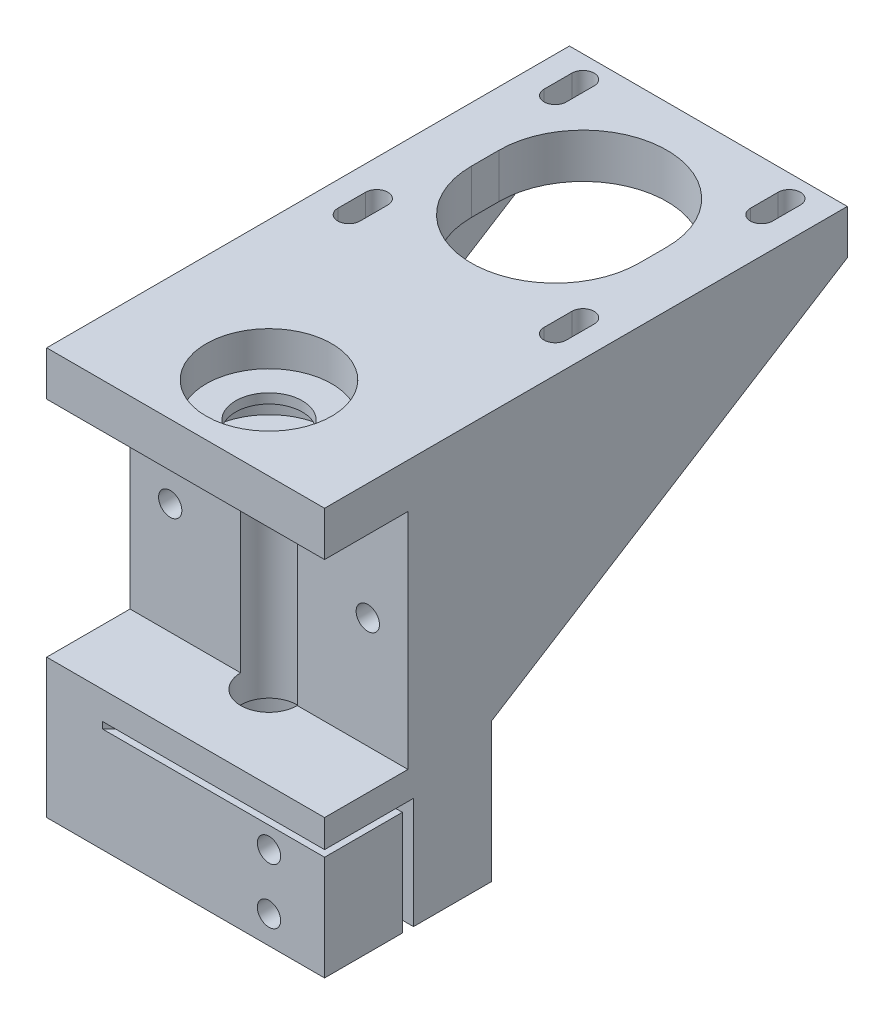
SolidWorks part; units mm, degrees
ref_plane "Front Plane" through (0, 0, 0) normal (0, 0, 1) x (1, 0, 0)
ref_plane "Top Plane" through (0, 0, 0) normal (0, 1, 0) x (1, 0, 0)
ref_plane "Right Plane" through (0, 0, 0) normal (1, 0, 0) x (0, 0, -1)
sketch "Sketch1" plane through (0, 0, 0) normal (0, 1, 0) x (1, 0, 0)
  line L1 (-25.4, -19.05) -> (25.4, -19.05)
  line L2 (-25.4, -19.05) -> (-25.4, 19.05)
  line L3 (-25.4, 19.05) -> (25.4, 19.05)
  line L4 (25.4, -19.05) -> (25.4, 19.05)
  line L5 (-25.4, -19.05) -> (25.4, 19.05) construction
  line L6 (-25.4, 19.05) -> (25.4, -19.05) construction
  circle A0 centre (0, 0) radius 13.335
  dimension "D3" = 19.05
  dimension "D2" = 25.4
  dimension "D1" = 26.67
extrude "Boss-Extrude2" add sketch "Sketch1" along normal blind 25.4
sketch "Sketch2" plane through (0, 25.4, 0) normal (0, 1, 0) x (1, 0, 0)
  line L0 (0, 0) -> (25.4, 0) construction
  line L1 (25.4, -19.05) -> (25.4, 19.05) construction
  line L2 (0, -1.27) -> (25.4, -1.27)
  line L3 (0, 1.27) -> (25.4, 1.27)
  line L4 (0, 1.27) -> (0, -1.27)
  line L5 (25.4, -1.27) -> (25.4, 1.27)
  dimension "D1" = 1.27
  dimension "D2" = 1.27
extrude "Cut-Extrude1" cut sketch "Sketch2" against normal up to next
sketch "Sketch3" plane through (0, 0, 19.05) normal (0, 0, 1) x (1, 0, 0)
  line L0 (-25.4, 25.4) -> (25.4, 25.4) construction
  line L1 (25.4, 25.4) -> (25.4, 0) construction
  line L2 (-25.4, 0) -> (25.4, 0) construction
  circle A0 centre (19.05, 19.05) radius 2.665
  circle A1 centre (19.05, 6.35) radius 2.665
  dimension "D1" = 5.33
  dimension "D2" = 6.35
  dimension "D3" = 6.35
  dimension "D4" = 6.35
  dimension "D5" = 6.35
extrude "Cut-Extrude2" cut sketch "Sketch3" against normal through all
sketch "Sketch4" plane through (0, 0, -19.05) normal (0, 0, -1) x (-1, 0, 0)
  line L1 (-19.05, 24.8235) -> (-24.05, 21.9368)
  line L2 (-24.05, 21.9368) -> (-24.05, 16.1632)
  line L3 (-24.05, 16.1632) -> (-19.05, 13.2765)
  line L4 (-19.05, 13.2765) -> (-14.05, 16.1632)
  line L5 (-14.05, 16.1632) -> (-14.05, 21.9368)
  line L6 (-14.05, 21.9368) -> (-19.05, 24.8235)
  line L7 (-19.05, 12.1235) -> (-24.05, 9.2368)
  line L8 (-24.05, 9.2368) -> (-24.05, 3.4632)
  line L9 (-24.05, 3.4632) -> (-19.05, 0.5765)
  line L10 (-19.05, 0.5765) -> (-14.05, 3.4632)
  line L11 (-14.05, 3.4632) -> (-14.05, 9.2368)
  line L12 (-14.05, 9.2368) -> (-19.05, 12.1235)
  circle A0 centre (-19.05, 19.05) radius 5 construction
  circle A1 centre (-19.05, 6.35) radius 5 construction
  dimension "D1" = 10
extrude "Cut-Extrude3" cut sketch "Sketch4" against normal blind 10
sketch "Sketch5" plane through (0, 25.4, 0) normal (0, 1, 0) x (1, 0, 0)
  line L0 (-19.05, -19.05) -> (-9.4293, -9.4293)
  line L1 (-25.4, -19.05) -> (25.4, -19.05) construction
  line L2 (-25.4, 19.05) -> (-25.4, -19.05) construction
  line L3 (25.4, -19.05) -> (25.4, -1.27) construction
  line L4 (13.2744, -1.27) -> (25.4, -1.27) construction
  line L5 (-19.05, -19.05) -> (25.4, -19.05)
  line L6 (25.4, -19.05) -> (25.4, -1.27)
  line L7 (13.2744, -1.27) -> (25.4, -1.27)
  arc A0 (13.2744, 1.27) -> (13.2744, -1.27) centre (0, 0) ccw construction
  arc A1 (-9.4293, -9.4293) -> (13.2744, -1.27) centre (0, 0) ccw
  dimension "D1" = 6.35
  dimension "D2" = 45
extrude "Cut-Extrude4" cut sketch "Sketch5" against normal blind 1.5
sketch "Sketch6" plane through (0, 25.4, 0) normal (0, 1, 0) x (1, 0, 0)
  line L1 (25.4, -19.05) -> (-25.4, -19.05)
  line L2 (25.4, -19.05) -> (25.4, 19.05)
  line L3 (25.4, 19.05) -> (-25.4, 19.05)
  line L4 (-25.4, -19.05) -> (-25.4, 19.05)
  circle A0 centre (0, 0) radius 6.477
  dimension "D1" = 12.954
extrude "Boss-Extrude3" add sketch "Sketch6" along normal blind 6.35
sketch "Sketch8" plane through (0, 31.75, 0) normal (0, 1, 0) x (1, 0, 0)
  line L0 (25.4, -19.05) -> (25.4, 19.05) construction
  line L1 (-25.4, 19.05) -> (25.4, 19.05)
  line L2 (-25.4, 19.05) -> (-25.4, 0)
  line L3 (-25.4, 0) -> (-6.477, 0)
  line L4 (25.4, 19.05) -> (25.4, 0)
  line L5 (6.477, 0) -> (25.4, 0)
  arc A0 (6.477, 0) -> (-6.477, 0) centre (0, 0) ccw
extrude "Boss-Extrude4" add sketch "Sketch8" along normal blind 44.45
sketch "Sketch10" plane through (0, 76.2, 0) normal (0, 1, 0) x (1, 0, 0)
  line L5 (-25.4, 19.05) -> (-25.4, 0)
  line L6 (-25.4, 0) -> (-6.477, 0)
  line L7 (6.477, 0) -> (25.4, 0)
  line L8 (25.4, 0) -> (25.4, 19.05)
  line L9 (25.4, 19.05) -> (-25.4, 19.05)
  line L10 (-25.4, 19.05) -> (-25.4, 0)
  line L11 (-25.4, 0) -> (-13.97, 0)
  line L12 (13.97, 0) -> (25.4, 0)
  line L13 (25.4, 0) -> (25.4, 19.05)
  line L14 (25.4, 19.05) -> (-25.4, 19.05)
  arc A0 (13.97, 0) -> (-13.97, 0) centre (0, 0) ccw
  arc A2 (6.477, 0) -> (-6.477, 0) centre (0, 0) ccw
  dimension "D2" = 27.94
  dimension "D1" = 0
extrude "Boss-Extrude5" add sketch "Sketch10" along normal blind 6.604
sketch "Sketch11" plane through (0, 82.804, 0) normal (0, 1, 0) x (1, 0, 0)
  line L0 (0, -19.05) -> (0, 107.95) construction
  line L1 (28.575, -19.05) -> (-28.575, -19.05)
  line L2 (28.575, -19.05) -> (28.575, 107.95)
  line L3 (28.575, 107.95) -> (-28.575, 107.95)
  line L4 (-28.575, -19.05) -> (-28.575, 107.95)
  line L5 (0, 19.05) -> (0, 0) construction
  line L6 (25.4, 19.05) -> (-25.4, 19.05) construction
  line L7 (-25.4, -19.05) -> (25.4, -19.05) construction
  dimension "D1" = 57.15
  dimension "D2" = 127
extrude "Boss-Extrude6" add sketch "Sketch11" along normal blind 10.16
sketch "Sketch12" plane through (0, 92.964, 0) normal (0, 1, 0) x (1, 0, 0)
  arc A0 (6.477, 0) -> (-6.477, 0) centre (0, 0) ccw construction
  arc A1 (6.477, 0) -> (-6.477, 0) centre (0, 0) ccw construction
  circle A2 centre (0, 0) radius 7.62
  dimension "D1" = 15.24
extrude "Cut-Extrude6" cut sketch "Sketch12" against normal up to next
sketch "Sketch13" plane through (0, 92.964, 0) normal (0, 1, 0) x (1, 0, 0)
  circle A0 centre (0, 0) radius 14.351
  dimension "D1" = 28.702
extrude "Cut-Extrude7" cut sketch "Sketch13" against normal blind 7.9375
sketch "Sketch14" plane through (0, 92.964, 0) normal (0, 1, 0) x (1, 0, 0)
  line L0 (0, 65.405) -> (0, 71.755) construction
  line L1 (-19.177, 65.405) -> (-19.177, 71.755)
  line L2 (19.177, 65.405) -> (19.177, 71.755)
  arc A0 (-19.177, 65.405) -> (19.177, 65.405) centre (0, 65.405) ccw
  arc A1 (19.177, 71.755) -> (-19.177, 71.755) centre (0, 71.755) ccw
  circle A2 centre (0, 0) radius 14.351 construction
  point P3 (0, 68.58)
  dimension "D2" = 38.354
  dimension "D1" = 65.405
  dimension "D3" = 6.35
extrude "Cut-Extrude8" cut sketch "Sketch14" against normal up to next
sketch "Sketch15" plane through (0, 82.804, 0) normal (0, -1, 0) x (1, 0, 0)
  line L0 (-23.57, -88.975) -> (-23.57, -95.325) construction
  line L1 (-21.03, -88.975) -> (-21.03, -95.325)
  line L2 (-26.11, -88.975) -> (-26.11, -95.325)
  line L3 (23.57, -88.975) -> (23.57, -95.325) construction
  line L4 (26.11, -88.975) -> (26.11, -95.325)
  line L5 (21.03, -88.975) -> (21.03, -95.325)
  line L6 (23.57, -41.835) -> (23.57, -48.185) construction
  line L7 (26.11, -41.835) -> (26.11, -48.185)
  line L8 (21.03, -41.835) -> (21.03, -48.185)
  line L9 (-23.57, -41.835) -> (-23.57, -48.185) construction
  line L10 (-21.03, -41.835) -> (-21.03, -48.185)
  line L11 (-26.11, -41.835) -> (-26.11, -48.185)
  line L12 (23.57, -41.835) -> (26.1445, -41.835) construction
  line L13 (-21.07, -88.975) -> (-26.07, -88.975) construction
  circle A0 centre (23.57, -88.975) radius 2.5 construction
  circle A1 centre (23.57, -88.975) radius 2.5 construction
  circle A2 centre (-23.57, -41.835) radius 2.5 construction
  circle A3 centre (-23.57, -41.835) radius 2.5 construction
  arc A4 (-21.03, -88.975) -> (-26.11, -88.975) centre (-23.57, -88.975) ccw
  arc A5 (-26.11, -95.325) -> (-21.03, -95.325) centre (-23.57, -95.325) ccw
  arc A6 (26.11, -88.975) -> (21.03, -88.975) centre (23.57, -88.975) ccw
  arc A7 (21.03, -95.325) -> (26.11, -95.325) centre (23.57, -95.325) ccw
  arc A8 (26.11, -41.835) -> (21.03, -41.835) centre (23.57, -41.835) ccw
  arc A9 (21.03, -48.185) -> (26.11, -48.185) centre (23.57, -48.185) ccw
  arc A10 (-21.03, -41.835) -> (-26.11, -41.835) centre (-23.57, -41.835) ccw
  arc A11 (-26.11, -48.185) -> (-21.03, -48.185) centre (-23.57, -48.185) ccw
  circle A12 centre (23.57, -41.835) radius 2.5 construction
  spline S0 degree 3 poles (26.0411, -42.3063) (26.0845, -41.8349) (26.0411, -41.3636) (25.9042, -40.8968) (25.675, -40.4522) (25.3496, -40.0552) (24.9526, -39.7299) (24.5079, -39.5007) (24.0413, -39.3639) (23.5698, -39.3205) (23.0986, -39.3639) (22.6317, -39.5009) (22.1872, -39.73) (21.7902, -40.0554) (21.4649, -40.4524) (21.2357, -40.8971) (21.0989, -41.3637) (21.0555, -41.8352) (21.0989, -42.3064) (21.2359, -42.7733) (21.465, -43.2178) (21.7904, -43.6148) (22.1874, -43.9401) (22.6321, -44.1693) (23.0987, -44.3061) (23.5702, -44.3495) (24.0414, -44.3061) (24.5083, -44.1691) (24.9528, -43.94) (25.3498, -43.6146) (25.6751, -43.2176) (25.9043, -42.773) (26.0411, -42.3063) (26.0845, -41.8349) (26.0411, -41.3636) knots -0.092484 -0.060002 -0.029992 0 0.030009 0.060002 0.092518 0.125 0.157516 0.189998 0.220016 0.25 0.280018 0.310002 0.342518 0.375 0.407516 0.439998 0.470016 0.5 0.530018 0.560002 0.592518 0.625 0.657516 0.689998 0.720016 0.75 0.780018 0.810002 0.842518 0.875 0.907516 0.939998 0.970008 1 1.030009 1.060002 1.092518 only from (26.07, -41.835) to (26.07, -41.835) construction
  spline S1 degree 3 poles (26.0411, -42.3063) (26.0845, -41.8349) (26.0411, -41.3636) (25.9042, -40.8968) (25.675, -40.4522) (25.3496, -40.0552) (24.9526, -39.7299) (24.5079, -39.5007) (24.0413, -39.3639) (23.5698, -39.3205) (23.0986, -39.3639) (22.6317, -39.5009) (22.1872, -39.73) (21.7902, -40.0554) (21.4649, -40.4524) (21.2357, -40.8971) (21.0989, -41.3637) (21.0555, -41.8352) (21.0989, -42.3064) (21.2359, -42.7733) (21.465, -43.2178) (21.7904, -43.6148) (22.1874, -43.9401) (22.6321, -44.1693) (23.0987, -44.3061) (23.5702, -44.3495) (24.0414, -44.3061) (24.5083, -44.1691) (24.9528, -43.94) (25.3498, -43.6146) (25.6751, -43.2176) (25.9043, -42.773) (26.0411, -42.3063) (26.0845, -41.8349) (26.0411, -41.3636) knots -0.092484 -0.060002 -0.029992 0 0.030009 0.060002 0.092518 0.125 0.157516 0.189998 0.220016 0.25 0.280018 0.310002 0.342518 0.375 0.407516 0.439998 0.470016 0.5 0.530018 0.560002 0.592518 0.625 0.657516 0.689998 0.720016 0.75 0.780018 0.810002 0.842518 0.875 0.907516 0.939998 0.970008 1 1.030009 1.060002 1.092518 only from (26.07, -41.835) to (26.07, -41.835) construction
  spline S2 degree 3 poles (-21.0989, -89.4463) (-21.0555, -88.9749) (-21.0989, -88.5036) (-21.2358, -88.0368) (-21.465, -87.5922) (-21.7904, -87.1952) (-22.1874, -86.8699) (-22.6321, -86.6407) (-23.0987, -86.5039) (-23.5702, -86.4605) (-24.0414, -86.5039) (-24.5083, -86.6409) (-24.9528, -86.87) (-25.3498, -87.1954) (-25.6751, -87.5924) (-25.9043, -88.0371) (-26.0411, -88.5037) (-26.0845, -88.9752) (-26.0411, -89.4464) (-25.9041, -89.9133) (-25.675, -90.3578) (-25.3496, -90.7548) (-24.9526, -91.0801) (-24.5079, -91.3093) (-24.0413, -91.4461) (-23.5698, -91.4895) (-23.0986, -91.4461) (-22.6317, -91.3091) (-22.1872, -91.08) (-21.7902, -90.7546) (-21.4649, -90.3576) (-21.2357, -89.913) (-21.0989, -89.4463) (-21.0555, -88.9749) (-21.0989, -88.5036) knots -0.092484 -0.060002 -0.029992 0 0.030009 0.060002 0.092518 0.125 0.157516 0.189998 0.220016 0.25 0.280018 0.310002 0.342518 0.375 0.407516 0.439998 0.470016 0.5 0.530018 0.560002 0.592518 0.625 0.657516 0.689998 0.720016 0.75 0.780018 0.810002 0.842518 0.875 0.907516 0.939998 0.970008 1 1.030009 1.060002 1.092518 only from (-21.07, -88.975) to (-21.07, -88.975) construction
  spline S3 degree 3 poles (-21.0989, -89.4463) (-21.0555, -88.9749) (-21.0989, -88.5036) (-21.2358, -88.0368) (-21.465, -87.5922) (-21.7904, -87.1952) (-22.1874, -86.8699) (-22.6321, -86.6407) (-23.0987, -86.5039) (-23.5702, -86.4605) (-24.0414, -86.5039) (-24.5083, -86.6409) (-24.9528, -86.87) (-25.3498, -87.1954) (-25.6751, -87.5924) (-25.9043, -88.0371) (-26.0411, -88.5037) (-26.0845, -88.9752) (-26.0411, -89.4464) (-25.9041, -89.9133) (-25.675, -90.3578) (-25.3496, -90.7548) (-24.9526, -91.0801) (-24.5079, -91.3093) (-24.0413, -91.4461) (-23.5698, -91.4895) (-23.0986, -91.4461) (-22.6317, -91.3091) (-22.1872, -91.08) (-21.7902, -90.7546) (-21.4649, -90.3576) (-21.2357, -89.913) (-21.0989, -89.4463) (-21.0555, -88.9749) (-21.0989, -88.5036) knots -0.092484 -0.060002 -0.029992 0 0.030009 0.060002 0.092518 0.125 0.157516 0.189998 0.220016 0.25 0.280018 0.310002 0.342518 0.375 0.407516 0.439998 0.470016 0.5 0.530018 0.560002 0.592518 0.625 0.657516 0.689998 0.720016 0.75 0.780018 0.810002 0.842518 0.875 0.907516 0.939998 0.970008 1 1.030009 1.060002 1.092518 only from (-21.07, -88.975) to (-21.07, -88.975) construction
  point P10 (-23.57, -92.15)
  point P15 (23.57, -92.15)
  point P21 (23.57, -45.01)
  point P28 (-23.57, -45.01)
  dimension "D1" = 6.35
  dimension "D2" = 5.08
extrude "Cut-Extrude11" cut sketch "Sketch15" against normal up to next
sketch "Sketch16" plane through (0, 92.964, 0) normal (0, 1, 0) x (1, 0, 0)
  line L0 (28.575, -19.05) -> (28.575, 107.95) construction
  line L1 (-28.575, 107.95) -> (28.575, 107.95)
  line L2 (-28.575, 107.95) -> (-28.575, 100.405)
  line L3 (-28.575, 100.405) -> (28.575, 100.405)
  line L4 (28.575, 107.95) -> (28.575, 100.405)
  arc A0 (26.11, 95.325) -> (21.03, 95.325) centre (23.57, 95.325) ccw construction
  dimension "D1" = 5.08
extrude "Cut-Extrude12" cut sketch "Sketch16" against normal up to next
sketch "Sketch17" plane through (25.4, 0, 0) normal (1, 0, 0) x (0, 0, -1)
  line L0 (-1.27, 23.9) -> (-19.05, 23.9) construction
  line L1 (-19.05, 23.9) -> (-19.05, 0) construction
  line L2 (-19.05, 0) -> (-1.27, 0) construction
  line L3 (-1.27, 0) -> (-1.27, 23.9) construction
  line L4 (19.05, 0) -> (19.05, 82.804) construction
  line L5 (19.05, 82.804) -> (0, 82.804) construction
  line L6 (0, 82.804) -> (0, 31.75) construction
  line L7 (0, 31.75) -> (-19.05, 31.75) construction
  line L8 (-19.05, 31.75) -> (-19.05, 25.4) construction
  line L9 (-19.05, 25.4) -> (1.27, 25.4) construction
  line L10 (1.27, 25.4) -> (1.27, 0) construction
  line L11 (1.27, 0) -> (19.05, 0) construction
  line L12 (-1.27, 23.9) -> (-19.05, 23.9)
  line L13 (-19.05, 23.9) -> (-19.05, 0)
  line L14 (-19.05, 0) -> (-1.27, 0)
  line L15 (-1.27, 0) -> (-1.27, 23.9)
  line L16 (19.05, 0) -> (19.05, 82.804)
  line L17 (19.05, 82.804) -> (0, 82.804)
  line L18 (0, 82.804) -> (0, 31.75)
  line L19 (0, 31.75) -> (-19.05, 31.75)
  line L20 (-19.05, 31.75) -> (-19.05, 25.4)
  line L21 (-19.05, 25.4) -> (1.27, 25.4)
  line L22 (1.27, 25.4) -> (1.27, 0)
  line L23 (1.27, 0) -> (19.05, 0)
extrude "Boss-Extrude7" add sketch "Sketch17" along normal up to surface (3.175 mm away) up to face at (28.575, 87.884, -40.6775)
sketch "Sketch18" plane through (-25.4, 0, 0) normal (-1, 0, 0) x (0, 0, 1)
  line L6 (-19.05, 0) -> (19.05, 0)
  line L7 (19.05, 0) -> (19.05, 31.75)
  line L8 (19.05, 31.75) -> (0, 31.75)
  line L9 (0, 31.75) -> (0, 82.804)
  line L10 (0, 82.804) -> (-19.05, 82.804)
  line L11 (-19.05, 82.804) -> (-19.05, 0)
  line L12 (-19.05, 0) -> (19.05, 0)
  line L13 (19.05, 0) -> (19.05, 31.75)
  line L14 (19.05, 31.75) -> (0, 31.75)
  line L15 (0, 31.75) -> (0, 82.804)
  line L16 (0, 82.804) -> (-19.05, 82.804)
  line L17 (-19.05, 82.804) -> (-19.05, 0)
  dimension "D1" = 0
extrude "Boss-Extrude8" add sketch "Sketch18" along normal up to surface (3.175 mm away) up to face at (-28.575, 87.884, -40.6775)
sketch "Sketch19" plane through (-28.575, 0, 0) normal (-1, 0, 0) x (0, 0, 1)
  line L0 (-100.405, 92.964) -> (0, 92.964)
  line L1 (-100.405, 92.964) -> (19.05, 92.964) construction
  line L2 (0, 82.804) -> (0, 31.75)
  line L3 (0, 31.75) -> (-19.05, 31.75) construction
  line L4 (-19.05, 0) -> (-19.05, 82.804) construction
  line L5 (-19.05, 31.75) -> (-100.405, 82.804)
  line L6 (-100.405, 82.804) -> (-100.405, 92.964)
  line L17 (19.05, 92.964) -> (-100.405, 92.964)
  line L18 (-100.405, 92.964) -> (-100.405, 82.804)
  line L19 (-100.405, 82.804) -> (-19.05, 82.804)
  line L20 (-19.05, 82.804) -> (-19.05, 0)
  line L21 (-19.05, 0) -> (19.05, 0)
  line L22 (19.05, 0) -> (19.05, 31.75)
  line L23 (19.05, 31.75) -> (0, 31.75)
  line L24 (0, 31.75) -> (0, 82.804)
  line L25 (0, 82.804) -> (19.05, 82.804)
  line L26 (19.05, 82.804) -> (19.05, 92.964)
  line L27 (19.05, 92.964) -> (-100.405, 92.964)
  line L28 (-100.405, 92.964) -> (-100.405, 82.804)
  line L30 (-19.05, 31.75) -> (-19.05, 0)
  line L31 (-19.05, 0) -> (19.05, 0)
  line L32 (19.05, 0) -> (19.05, 31.75)
  line L33 (19.05, 31.75) -> (0, 31.75)
  line L34 (0, 31.75) -> (0, 82.804)
  line L35 (0, 82.804) -> (19.05, 82.804)
  line L36 (19.05, 82.804) -> (19.05, 92.964)
  line M1 (19.05, 92.964) -> (-100.405, 92.964)
  line M2 (-100.405, 92.964) -> (-100.405, 82.804)
  line M3 (-100.405, 82.804) -> (-19.05, 82.804)
  line M4 (-19.05, 82.804) -> (-19.05, 0)
  line M5 (-19.05, 0) -> (19.05, 0)
  line M6 (19.05, 0) -> (19.05, 31.75)
  line M7 (19.05, 31.75) -> (0, 31.75)
  line M8 (0, 31.75) -> (0, 82.804)
  line M9 (0, 82.804) -> (19.05, 82.804)
  line M10 (19.05, 82.804) -> (19.05, 92.964)
  dimension "D1" = 0
extrude "Boss-Extrude10" add sketch "Sketch19" along normal blind 3.175 contours L3 M8 M9 M10 M1 M2 M3 M4 | L3 M7 M4 M5 M6 | L5 M4 M3
sketch "Sketch20" plane through (28.575, 0, 0) normal (1, 0, 0) x (0, 0, -1)
  line L0 (0, 31.75) -> (19.05, 31.75) construction
  line L1 (19.05, 31.75) -> (100.405, 82.804)
  line L4 (-1.27, 23.9) -> (-19.05, 23.9)
  line L5 (-19.05, 23.9) -> (-19.05, 0)
  line L6 (-19.05, 0) -> (-1.27, 0)
  line L7 (-1.27, 0) -> (-1.27, 23.9)
  line L8 (-1.27, 23.9) -> (-19.05, 23.9)
  line L9 (-19.05, 23.9) -> (-19.05, 0)
  line L10 (-19.05, 0) -> (-1.27, 0)
  line L11 (-1.27, 0) -> (-1.27, 23.9)
  line L12 (-19.05, 82.804) -> (0, 82.804)
  line L13 (0, 82.804) -> (0, 31.75)
  line L14 (0, 31.75) -> (-19.05, 31.75)
  line L15 (-19.05, 31.75) -> (-19.05, 25.4)
  line L16 (-19.05, 25.4) -> (1.27, 25.4)
  line L17 (1.27, 25.4) -> (1.27, 0)
  line L18 (1.27, 0) -> (19.05, 0)
  line L19 (19.05, 0) -> (19.05, 82.804)
  line L20 (19.05, 82.804) -> (100.405, 82.804)
  line L21 (100.405, 82.804) -> (100.405, 92.964)
  line L22 (100.405, 92.964) -> (-19.05, 92.964)
  line L23 (-19.05, 92.964) -> (-19.05, 82.804)
  line L24 (-19.05, 82.804) -> (0, 82.804)
  line L25 (0, 82.804) -> (0, 31.75)
  line L26 (0, 31.75) -> (-19.05, 31.75)
  line L27 (-19.05, 31.75) -> (-19.05, 25.4)
  line L28 (-19.05, 25.4) -> (1.27, 25.4)
  line L29 (1.27, 25.4) -> (1.27, 0)
  line L30 (1.27, 0) -> (19.05, 0)
  line L31 (19.05, 0) -> (19.05, 31.75)
  line L33 (100.405, 82.804) -> (100.405, 92.964)
  line L34 (100.405, 92.964) -> (-19.05, 92.964)
  line L35 (-19.05, 92.964) -> (-19.05, 82.804)
  dimension "D1" = 0
  dimension "D2" = 0
extrude "Boss-Extrude11" add sketch "Sketch20" along normal blind 3.175
sketch "Sketch21" plane through (0, 0, -19.05) normal (0, 0, -1) x (-1, 0, 0)
  line L0 (31.75, 31.75) -> (28.575, 31.75) construction
  line L1 (28.575, 31.75) -> (28.575, 82.804) construction
  line L2 (0, 82.804) -> (0, 0) construction
  line L3 (-28.575, 82.804) -> (28.575, 82.804) construction
  line L4 (-31.75, 0) -> (31.75, 0) construction
  circle A0 centre (22.575, 57.15) radius 2.665
  circle A1 centre (-22.575, 57.15) radius 2.665
  point P4 (30.1625, 31.75)
  dimension "D1" = 25.4
  dimension "D2" = 5.33
  dimension "D3" = 6
extrude "Cut-Extrude13" cut sketch "Sketch21" against normal up to next
